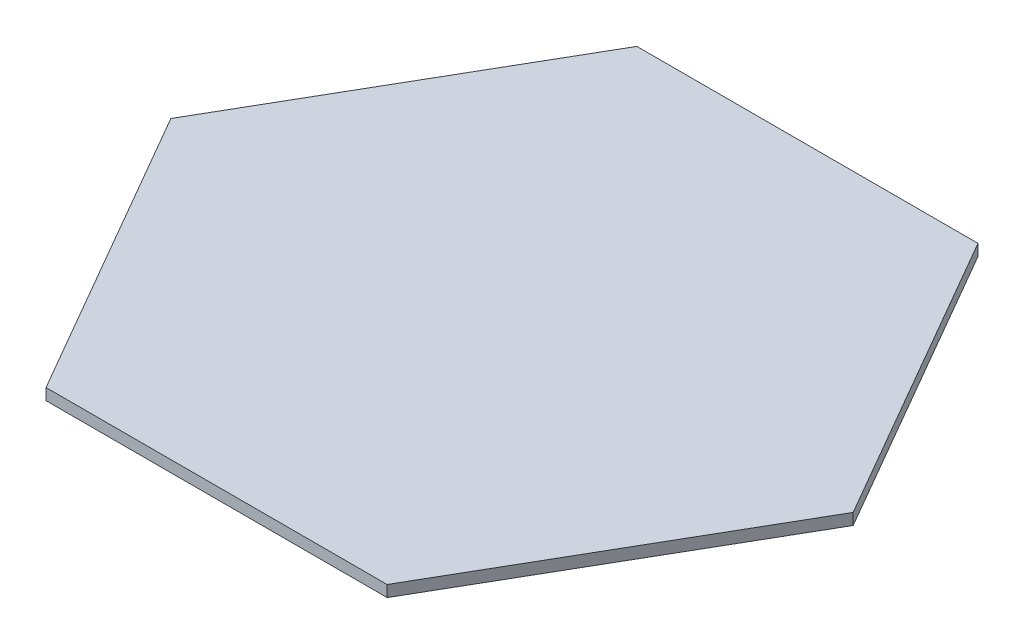
SolidWorks part; units mm, degrees
ref_plane "前视基准面" through (0, 0, 0) normal (0, 0, 1) x (1, 0, 0)
ref_plane "上视基准面" through (0, 0, 0) normal (0, 1, 0) x (1, 0, 0)
ref_plane "右视基准面" through (0, 0, 0) normal (1, 0, 0) x (0, 0, -1)
sketch "草图1" plane through (0, 0, 0) normal (0, 1, 0) x (1, 0, 0)
  line L1 (75, 0) -> (37.5, 64.9519)
  line L2 (37.5, 64.9519) -> (-37.5, 64.9519)
  line L3 (-37.5, 64.9519) -> (-75, 0)
  line L4 (-75, 0) -> (-37.5, -64.9519)
  line L5 (-37.5, -64.9519) -> (37.5, -64.9519)
  line L6 (37.5, -64.9519) -> (75, 0)
  circle A0 centre (0, 0) radius 64.9519 construction
  dimension "D1" = 75
extrude "凸台-拉伸1" add sketch "草图1" along normal blind 2.5
